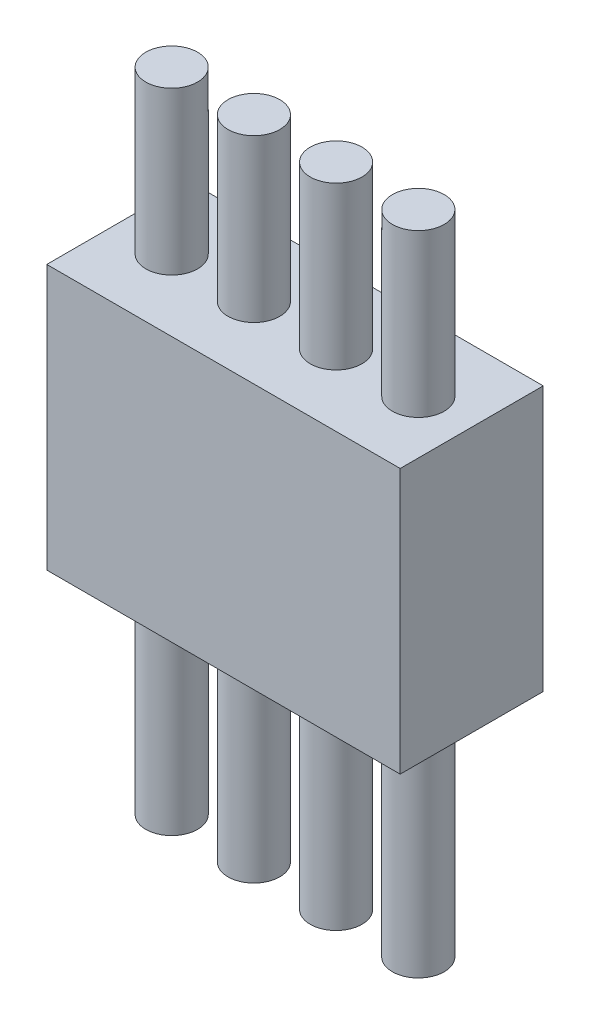
SolidWorks part; units mm, degrees
ref_plane "Front Plane" through (0, 0, 0) normal (0, 0, 1) x (1, 0, 0)
ref_plane "Top Plane" through (0, 0, 0) normal (0, 1, 0) x (1, 0, 0)
ref_plane "Right Plane" through (0, 0, 0) normal (1, 0, 0) x (0, 0, -1)
sketch "Sketch1" plane through (0, 0, 0) normal (0, 0, 1) x (1, 0, 0)
  line L1 (-2.73, 2.045) -> (2.73, 2.045)
  line L2 (-2.73, 2.045) -> (-2.73, -2.045)
  line L3 (-2.73, -2.045) -> (2.73, -2.045)
  line L4 (2.73, 2.045) -> (2.73, -2.045)
  line L5 (-2.73, 2.045) -> (2.73, -2.045) construction
  line L6 (-2.73, -2.045) -> (2.73, 2.045) construction
  point P0 (0, 0)
  dimension "D1" = 5.46
  dimension "D2" = 4.09
extrude "Boss-Extrude1" add sketch "Sketch1" along normal mid plane 2.21
sketch "Sketch2" plane through (0, 2.045, 0) normal (0, 1, 0) x (1, 0, 0)
  circle A0 centre (-1.905, 0) radius 0.4
  circle A1 centre (-0.635, 0) radius 0.4
  circle A2 centre (0.635, 0) radius 0.4
  circle A3 centre (1.905, 0) radius 0.4
  point P12 (0, 0)
  point P15 (0.7077, -0.044)
  dimension "D1" = 0.635
  dimension "D2" = 0.635
  dimension "D3" = 1.27
  dimension "D4" = 1.27
extrude "Boss-Extrude2" add sketch "Sketch2" along normal blind 10 from offset 7.5
